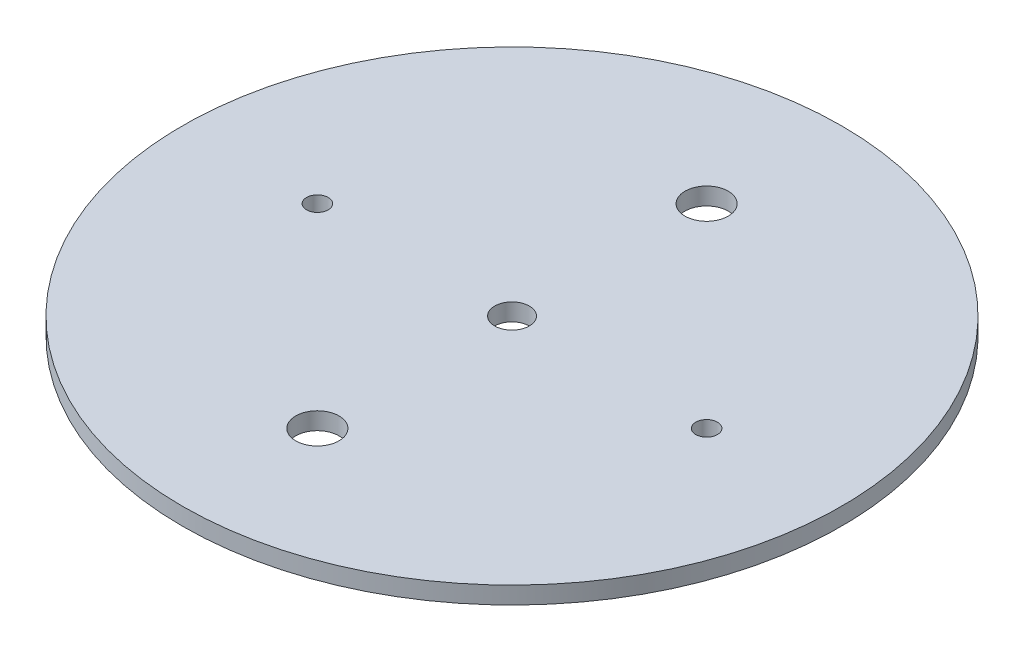
SolidWorks part; units mm, degrees
material "1060 Alloy"
ref_plane "Front Plane" through (0, 0, 0) normal (0, 0, 1) x (1, 0, 0)
ref_plane "Top Plane" through (0, 0, 0) normal (0, 1, 0) x (1, 0, 0)
ref_plane "Right Plane" through (0, 0, 0) normal (1, 0, 0) x (0, 0, -1)
sketch "Sketch1" plane through (0, 0, 0) normal (0, 1, 0) x (1, 0, 0)
  line L0 (45, 0) -> (-45, 0) construction
  line L1 (0, -45) -> (0, 0) construction
  circle A0 centre (0, 0) radius 76.2
  circle A1 centre (-45, 0) radius 2.5
  circle A2 centre (45, 0) radius 2.5
  circle A3 centre (0, 0) radius 4
  circle A4 centre (0, -45) radius 5
  circle A5 centre (0, 45) radius 5
  point P6 (0, 0)
  dimension "D1" = 152.4
  dimension "D2" = 5
  dimension "D3" = 5
  dimension "D5" = 8
  dimension "D6" = 10
  dimension "D4" = 90
  dimension "D7" = 45
extrude "Boss-Extrude1" add sketch "Sketch1" along normal blind 4
